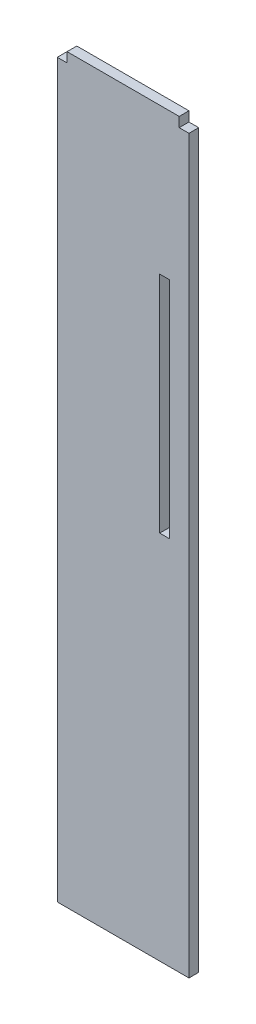
SolidWorks part; units mm, degrees
ref_plane "Front Plane" through (0, 0, 0) normal (0, 0, 1) x (1, 0, 0)
ref_plane "Top Plane" through (0, 0, 0) normal (0, 1, 0) x (1, 0, 0)
ref_plane "Right Plane" through (0, 0, 0) normal (1, 0, 0) x (0, 0, -1)
sketch "Sketch1" plane through (0, 0, 0) normal (0, 0, 1) x (1, 0, 0)
  line L0 (0, 300) -> (4, 300)
  line L1 (0, 0) -> (54, 0)
  line L2 (0, 0) -> (0, 300)
  line L4 (54, 0) -> (54, 300)
  line L5 (4, 300) -> (4, 304)
  line L6 (4, 304) -> (50, 304)
  line L7 (50, 304) -> (50, 300)
  line L8 (50, 300) -> (54, 300)
  point P9 (0, 0)
  dimension "D1" = 4
  dimension "D2" = 46
  dimension "D3" = 300
  dimension "D4" = 4
  dimension "D5" = 4
extrude "Boss-Extrude1" add sketch "Sketch1" along normal blind 4
sketch "Sketch2" plane through (0, 0, 4) normal (0, 0, 1) x (1, 0, 0)
  line L0 (54, 0) -> (54, 300) construction
  line L1 (46, 244) -> (42, 244)
  line L2 (46, 244) -> (46, 152)
  line L3 (46, 152) -> (42, 152)
  line L4 (42, 244) -> (42, 152)
  line L5 (50, 304) -> (4, 304) construction
  dimension "D1" = 92
  dimension "D2" = 4
  dimension "D3" = 8
  dimension "D4" = 60
extrude "Cut-Extrude1" cut sketch "Sketch2" against normal through all
